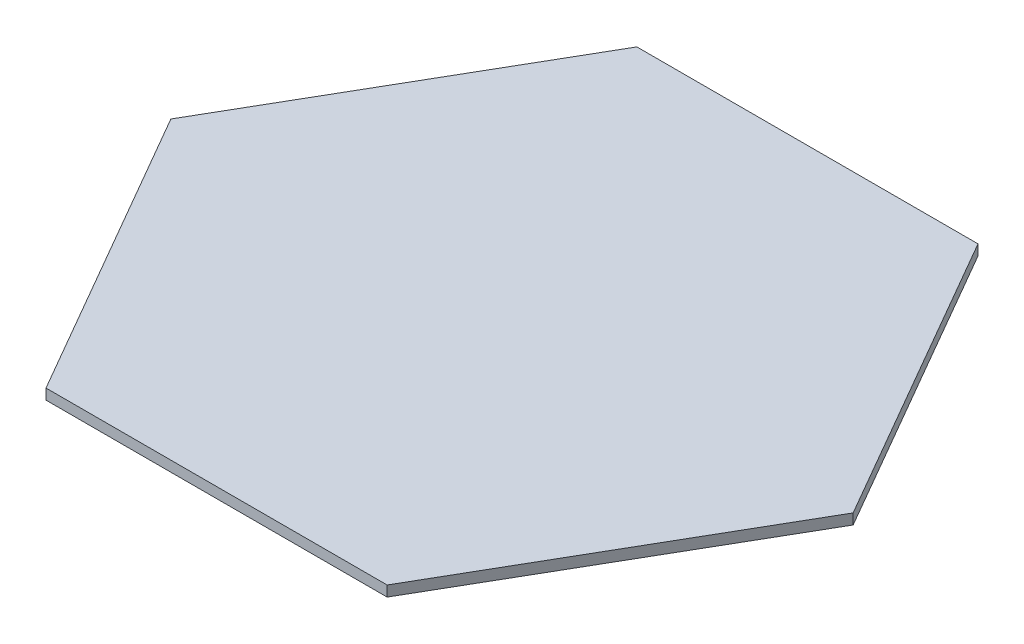
SolidWorks part; units mm, degrees
ref_plane "前视基准面" through (0, 0, 0) normal (0, 0, 1) x (1, 0, 0)
ref_plane "上视基准面" through (0, 0, 0) normal (0, 1, 0) x (1, 0, 0)
ref_plane "右视基准面" through (0, 0, 0) normal (1, 0, 0) x (0, 0, -1)
ref_plane "基准面1" through (0, -1, 0) normal (0, 1, 0) x (1, 0, 0)
sketch "草图1" plane through (0, -1, 0) normal (0, 1, 0) x (1, 0, 0)
  line L1 (65, 0) -> (32.5, 56.2917)
  line L2 (32.5, 56.2917) -> (-32.5, 56.2917)
  line L3 (-32.5, 56.2917) -> (-65, 0)
  line L4 (-65, 0) -> (-32.5, -56.2917)
  line L5 (-32.5, -56.2917) -> (32.5, -56.2917)
  line L6 (32.5, -56.2917) -> (65, 0)
  circle A0 centre (0, 0) radius 56.2917 construction
  dimension "D1" = 65
extrude "凸台-拉伸1" add sketch "草图1" against normal blind 2
